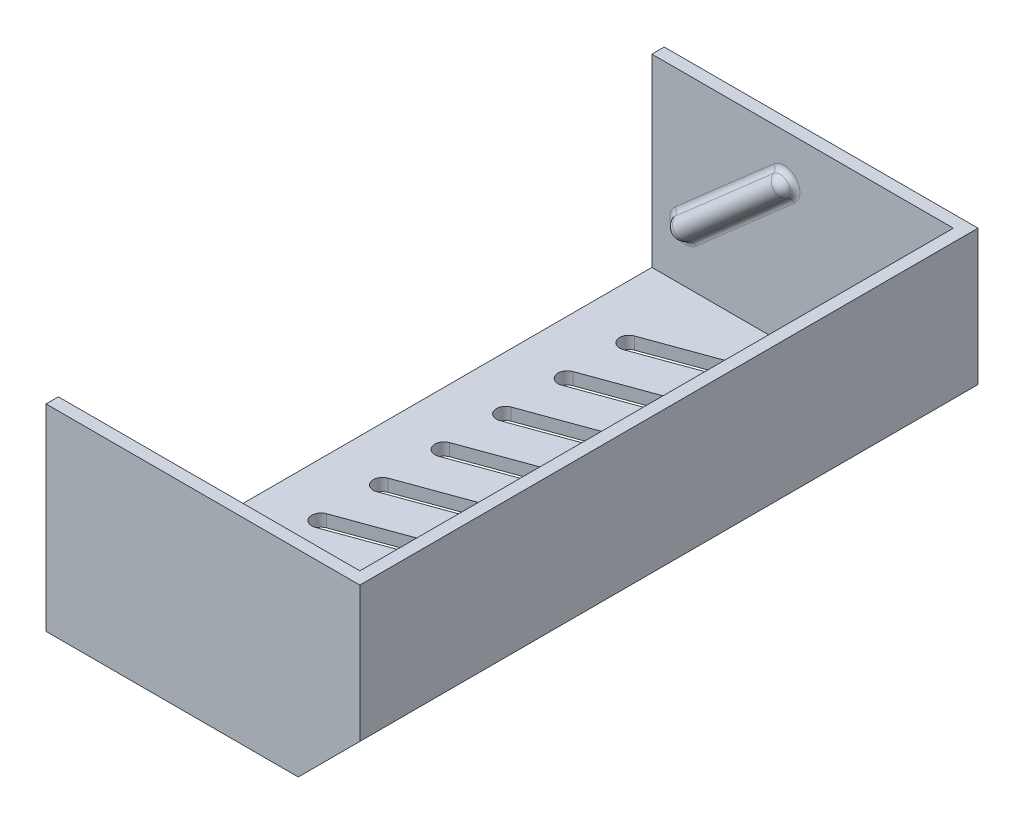
SolidWorks part; units mm, degrees
ref_plane "Front Plane" through (0, 0, 0) normal (0, 0, 1) x (1, 0, 0)
ref_plane "Top Plane" through (0, 0, 0) normal (0, 1, 0) x (1, 0, 0)
ref_plane "Right Plane" through (0, 0, 0) normal (1, 0, 0) x (0, 0, -1)
sketch "Sketch2" plane through (0, -30, 0) normal (0, -1, 0) x (1, 0, 0)
  line L0 (-133.57, -96) -> (-84.8, -96) construction
  line L1 (-84.8, -96) -> (-84.8, 0) construction
  line L2 (-84.8, 0) -> (-133.57, 0) construction
  line L3 (-133.57, 0) -> (-133.57, -96) construction
  line L4 (-133.57, 0) -> (-133.57, -96) construction
  line L6 (-133.57, -96.2) -> (-84.6, -96.2)
  line L7 (-84.6, -96.2) -> (-84.6, 0.2)
  line L8 (-84.6, 0.2) -> (-133.57, 0.2)
  line L9 (-133.57, -98.2) -> (-82.6, -98.2)
  line L10 (-82.6, -98.2) -> (-82.6, 2.2)
  line L11 (-82.6, 2.2) -> (-133.57, 2.2)
  line L12 (-133.57, -96.2) -> (-133.57, -98.2)
  line L13 (-133.57, 2.2) -> (-133.57, 0.2)
  line L14 (-138.14, -168) -> (-138.14, 72) construction
  line L15 (-78, 72) -> (-78, -168) construction
  dimension "D1" = 0.2
  dimension "D2" = 4.57
  dimension "D3" = 2
  dimension "D4" = 4.6
extrude "Boss-Extrude1" add sketch "Sketch2" against normal up to vertex (30 mm away)
sketch "Sketch3" plane through (0, -30, 0) normal (0, -1, 0) x (1, 0, 0)
  line L1 (-82.6, 2.2) -> (-133.57, 2.2)
  line L2 (-82.6, 2.2) -> (-82.6, -98.2)
  line L3 (-82.6, -98.2) -> (-133.57, -98.2)
  line L4 (-133.57, 2.2) -> (-133.57, -98.2)
extrude "Boss-Extrude2" add sketch "Sketch3" along normal blind 2
sketch "Sketch4" plane through (0, 0, 0.2) normal (0, 0, -1) x (-1, 0, 0)
  line L0 (129.416, -22.6692) -> (110.7729, -6.3156)
  line L1 (129.9106, -22.1054) -> (128.9214, -23.233) construction
  line L2 (111.2674, -5.7518) -> (110.2783, -6.8794) construction
  line L3 (128.1004, -21.5152) -> (112.0884, -7.4696) construction
  line L4 (126.9464, -22.8308) -> (110.9344, -8.7852)
  line L5 (129.2544, -20.1996) -> (113.2425, -6.154)
  line L6 (127.5102, -23.3253) -> (110.3706, -8.2906) construction
  arc A0 (126.9464, -22.8308) -> (129.2544, -20.1996) centre (128.1004, -21.5152) ccw
  arc A1 (113.2425, -6.154) -> (110.9344, -8.7852) centre (112.0884, -7.4696) ccw
  point P8 (120.0944, -14.4924)
revolve "Revolve1" add sketch "Sketch4" angle 358 about L3
ref_plane "Plane1" through (0, 0, -48) normal (0, 0, -1) x (-1, 0, 0)
mirror "Mirror3" about plane through (0, 0, -48) normal (0, 0, -1) of "Revolve1"
fillet "Fillet1" radius 1 8 edges at (-129.416, -22.6692, 0.2) (-118.9404, -15.808, 0.2) (-121.2484, -13.1768, 0.2) (-110.7729, -6.3156, 0.2) (-110.7729, -6.3156, -96.2) (-121.2484, -13.1768, -96.2) (-118.9404, -15.808, -96.2) (-129.416, -22.6692, -96.2)
sketch "Sketch5" plane through (0, 0, -98.2) normal (0, 0, -1) x (-1, 0, 0)
  line L0 (92.6, -32) -> (82.6, -22)
  line L1 (133.57, -32) -> (82.6, -32) construction
  line L2 (82.6, 0) -> (82.6, -32) construction
  line L3 (92.6, -32) -> (82.6, -32)
  line L4 (82.6, -32) -> (82.6, -22)
  dimension "D1" = 10
  dimension "D2" = 10
extrude "Cut-Extrude1" cut sketch "Sketch5" against normal blind 101
sketch "Sketch7" plane through (0, 0, 0.2) normal (0, 0, -1) x (-1, 0, 0)
  line L0 (93.4284, -30) -> (84.6, -21.1716)
  line L1 (133.57, -30) -> (90.6, -30) construction
  line L2 (84.6, 0) -> (84.6, -24) construction
  line L3 (84.6, -21.1716) -> (84.6, -24)
  line L4 (84.6, -24) -> (90.6, -30)
  line L5 (90.6, -30) -> (93.4284, -30)
  dimension "D1" = 2
extrude "Boss-Extrude3" add sketch "Sketch7" along normal up to next
sketch "Sketch8" plane through (0, -32, 0) normal (0, -1, 0) x (1, 0, 0)
  line L0 (-92.6, -48) -> (-133.57, -48) construction
  line L1 (-92.6, 2.2) -> (-92.6, -98.2) construction
  line L2 (-133.57, 2.2) -> (-133.57, -98.2) construction
  line L3 (-101.3388, -52.2753) -> (-124.8312, -43.7247) construction
  line L4 (-101.8519, -53.6848) -> (-125.3442, -45.1343)
  line L5 (-100.8258, -50.8657) -> (-124.3181, -42.3152)
  arc A0 (-101.8519, -53.6848) -> (-100.8258, -50.8657) centre (-101.3388, -52.2753) ccw
  arc A1 (-124.3181, -42.3152) -> (-125.3442, -45.1343) centre (-124.8312, -43.7247) ccw
  point P8 (-113.085, -48)
  dimension "D2" = 1.5
  dimension "D1" = 25
  dimension "D3" = 20
extrude "Cut-Extrude2" cut sketch "Sketch8" against normal blind 2
pattern_linear "LPattern1" count 5 spacing 10 along (0, 0, -1) of "Cut-Extrude2"
pattern_linear "LPattern2" count 5 spacing 10 along (0, 0, 1) of "Cut-Extrude2"
sketch "Sketch9" plane through (0, 0, -98.2) normal (0, 0, -1) x (-1, 0, 0)
  line L0 (127.1471, -27) -> (121.0904, -27)
  line L1 (121.0904, -27) -> (122.6765, -19.791)
  line L2 (122.6765, -19.791) -> (116.9464, -19.791)
  line L3 (116.9464, -19.791) -> (122.8118, -5)
  line L4 (122.8118, -5) -> (122.8118, -15.5832)
  line L5 (122.8118, -15.5832) -> (127.1471, -15.5832)
  line L6 (127.1471, -15.5832) -> (127.1471, -27)
  line L7 (111.051, -7) -> (111.051, -25.83) construction
  line L8 (127.1471, -5) -> (100.1434, -5) construction
  line L11 (113.0106, -12.6) -> (114.9702, -22.2)
  line L12 (127.1471, -27) -> (103.9198, -27) construction
  line L13 (133.57, -32) -> (92.6, -32) construction
  line L14 (133.57, 0) -> (82.6, 0) construction
  line L15 (109.0914, -12.6) -> (107.1318, -22.2)
  line L17 (114.9702, -22.2) -> (107.1318, -22.2)
  line L18 (109.0914, -12.6) -> (113.0106, -12.6)
  circle A0 centre (111.051, -7) radius 2
  circle A5 centre (111.051, -23) radius 4
  circle A6 centre (111.051, -13) radius 2
  dimension "D1" = 4
  dimension "D2" = 5
  dimension "D3" = 5
  dimension "D4" = 8
  dimension "D5" = 10
extrude "Cut-Extrude3" cut sketch "Sketch9" against normal blind 1 contours L0 L1 L2 L3 L4 L5 L6 | L17 L15 L18 L11 | A5 | A6 | A0
